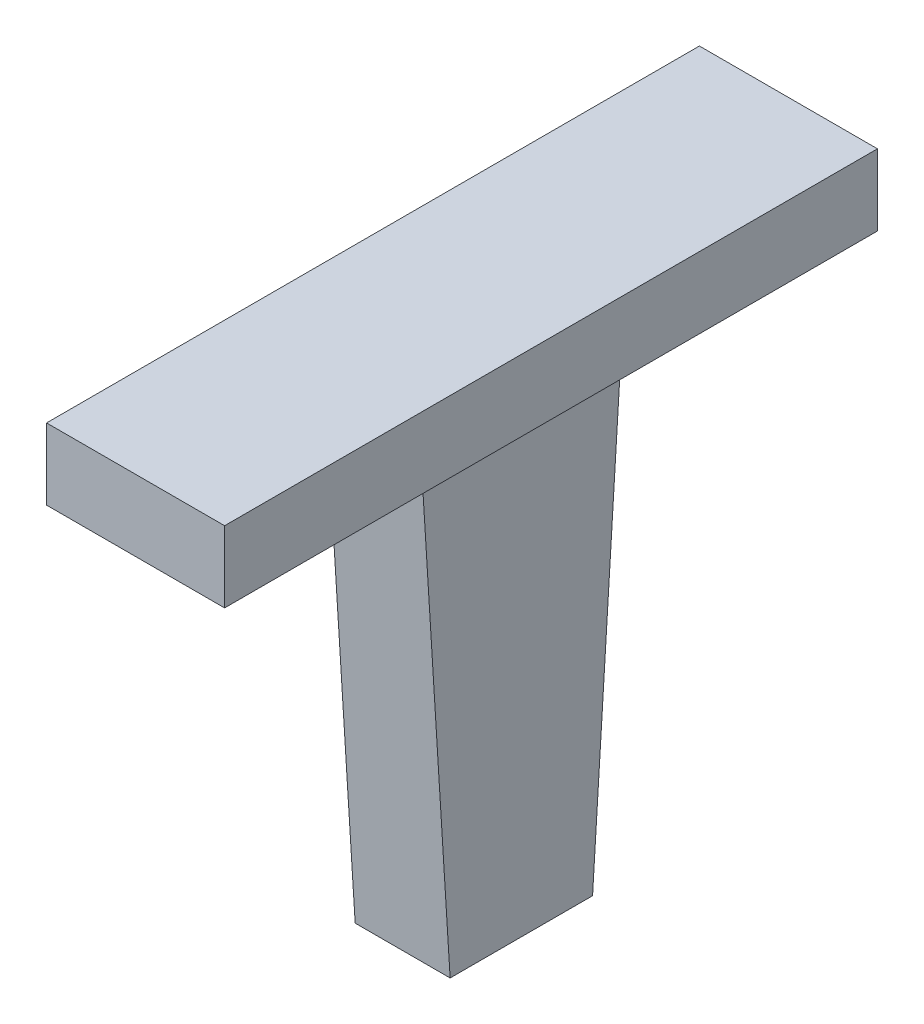
SolidWorks part; units mm, degrees
ref_plane "Front Plane" through (0, 0, 0) normal (0, 0, 1) x (1, 0, 0)
ref_plane "Top Plane" through (0, 0, 0) normal (0, 1, 0) x (1, 0, 0)
ref_plane "Right Plane" through (0, 0, 0) normal (1, 0, 0) x (0, 0, -1)
sketch "Sketch1" plane through (0, 0, 0) normal (1, 0, 0) x (0, 0, -1)
  line L0 (-30, 0) -> (30, 0)
  line L1 (30, 0) -> (42.5, 200)
  line L2 (42.5, 200) -> (132.5, 200)
  line L3 (132.5, 200) -> (132.5, 230)
  line L4 (132.5, 230) -> (-142.5, 230)
  line L5 (-142.5, 230) -> (-142.5, 200)
  line L6 (-142.5, 200) -> (-42.5, 200)
  line L7 (-42.5, 200) -> (-30, 0)
  line L8 (-42.5, 200) -> (42.5, 200) construction
  point P2 (0, 0)
  point P9 (0, 200)
  dimension "D1" = 60
  dimension "D2" = 200
  dimension "D3" = 85
  dimension "D4" = 30
  dimension "D5" = 90
  dimension "D6" = 100
extrude "Boss-Extrude1" add sketch "Sketch1" along normal blind 40
sketch "Sketch2" plane through (0, 0, 0) normal (1, 0, 0) x (0, 0, -1)
  line L1 (-142.5, 230) -> (132.5, 230)
  line L2 (-142.5, 230) -> (-142.5, 200)
  line L3 (-142.5, 200) -> (132.5, 200)
  line L4 (132.5, 230) -> (132.5, 200)
extrude "Boss-Extrude2" add sketch "Sketch2" along normal blind 75 from offset 17.5 offset against normal yes
sketch "Sketch4" plane through (0, 0, 0) normal (0, 1, 0) x (1, 0, 0)
  line L0 (40, 30) -> (0, 30) construction
  circle A0 centre (20, -10) radius 3.5
  circle A1 centre (20, 10) radius 3.5
  point P8 (20, 30)
  dimension "D2" = 10
  dimension "D3" = 7
  dimension "D1" = 10
extrude "Cut-Extrude1" cut sketch "Sketch4" along normal blind 10
